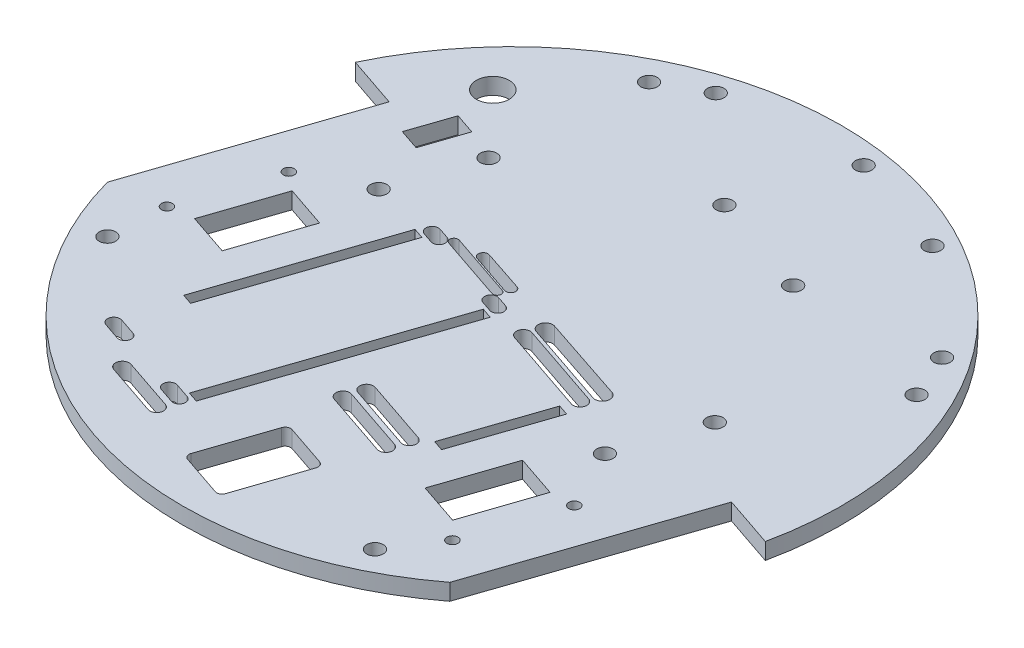
SolidWorks part; units mm, degrees
ref_plane "Alzado" through (0, 0, 0) normal (0, 0, 1) x (1, 0, 0)
ref_plane "Planta" through (0, 0, 0) normal (0, 1, 0) x (1, 0, 0)
ref_plane "Vista lateral" through (0, 0, 0) normal (1, 0, 0) x (0, 0, -1)
sketch "Croquis1" plane through (0, 0, 0) normal (0, 1, 0) x (1, 0, 0)
  line L12 (-65.7777, 23.2819) -> (-63.8527, 28.9647) construction
  line L13 (-25.7128, -75.9069) -> (39.5136, 116.648) construction
  line L15 (-54.221, 25.6922) -> (-44.913, 22.5392)
  line L16 (-44.913, 22.5392) -> (-57.8902, -15.771)
  line L17 (31.3298, -24.3939) -> (26.8382, -37.6538)
  line L18 (23.7528, -21.8272) -> (31.3298, -24.3939)
  line L19 (19.2611, -35.0871) -> (23.7528, -21.8272)
  line L20 (26.8382, -37.6538) -> (19.2611, -35.0871)
  line L21 (58.6729, -12.5497) -> (49.3649, -9.3967)
  line L22 (49.3649, -9.3967) -> (36.3876, -47.7068)
  line L32 (-2.2423, -26.9718) -> (9.5969, -30.9822)
  line L35 (4.6864, -0.2832) -> (20.3144, -5.577)
  line L36 (12.8273, -26.9004) -> (14.7216, -27.5421)
  line L38 (-3.0293, -29.3446) -> (8.7948, -33.35)
  line L39 (14.3923, -30.0726) -> (21.7715, -8.2885) construction
  line L41 (-44.197, -13.5912) -> (-36.6199, -16.1579)
  line L42 (-36.6199, -16.1579) -> (-32.1282, -2.898)
  line L43 (-32.1282, -2.898) -> (-39.7053, -0.3313)
  line L44 (-39.7053, -0.3313) -> (-44.197, -13.5912)
  line L45 (-44.197, -13.5912) -> (-36.6199, -16.1579)
  line L46 (-36.6199, -16.1579) -> (-32.1282, -2.898)
  line L47 (-32.1282, -2.898) -> (-39.7053, -0.3313)
  line L48 (-39.7053, -0.3313) -> (-44.197, -13.5912)
  line L51 (-27.8165, -44.7147) -> (-18.3452, -47.923)
  line L52 (-17.5431, -45.5552) -> (-27.0144, -42.3468)
  line L53 (14.7216, -27.5421) -> (20.4815, -10.5382)
  line L54 (20.4815, -10.5382) -> (18.5872, -9.8965)
  line L55 (18.5872, -9.8965) -> (12.8273, -26.9004)
  line L56 (-20.551, 4.1412) -> (-22.4453, 4.7829)
  line L57 (-10.7116, 5.3544) -> (-20.551, -23.6924) construction
  line L61 (-2.2537, 2.4893) -> (-19.1695, 8.2194) construction
  line L62 (-35.5833, -38.381) -> (-32.4839, -39.4309)
  line L63 (-22.4453, 4.7829) -> (-33.1017, -26.6759)
  line L64 (-33.1017, -26.6759) -> (-31.2074, -27.3176)
  line L65 (-31.2074, -27.3176) -> (-20.551, 4.1412)
  line L66 (-1.7409, -2.2305) -> (-12.3973, -33.6894)
  line L67 (-3.6352, -1.5889) -> (-1.7409, -2.2305)
  line L68 (-14.2916, -33.0477) -> (-3.6352, -1.5889)
  line L70 (-14.2916, -33.0477) -> (-17.1766, -41.5646)
  line L71 (-17.1766, -41.5646) -> (-15.2823, -42.2063)
  line L72 (-15.2823, -42.2063) -> (-12.3973, -33.6894)
  line L73 (-35.2168, 17.7539) -> (-32.6502, 25.331)
  line L74 (-7.4858, -50.9251) -> (-3.315, -38.6123)
  line L75 (-2.047, -37.986) -> (5.5301, -40.5527)
  line L76 (6.1564, -41.8207) -> (1.9855, -54.1334)
  line L77 (-6.8595, -52.193) -> (0.7176, -54.7597)
  line L78 (-32.6502, 25.331) -> (-36.4387, 26.6144)
  line L79 (-36.4387, 26.6144) -> (-39.0054, 19.0373)
  line L80 (-39.0054, 19.0373) -> (-35.2168, 17.7539)
  line L81 (-34.8498, -36.2158) -> (-31.7504, -37.2657)
  line L82 (-1.1514, -23.7515) -> (10.6878, -27.762)
  line L83 (-1.9535, -26.1194) -> (9.8857, -30.1298)
  line L84 (3.6918, -3.22) -> (19.3196, -8.5138)
  line L85 (4.4939, -0.8522) -> (20.1216, -6.1459)
  line L86 (-20.1813, 7.0872) -> (-18.287, 6.4455)
  line L87 (-20.9147, 4.922) -> (-19.0204, 4.2804)
  line L88 (-4.0326, 1.617) -> (-2.1384, 0.9753)
  line L89 (-4.7661, -0.5482) -> (-2.8718, -1.1899)
  line L90 (-19.5441, -41.4005) -> (-16.8069, -42.3277)
  line L91 (-20.2776, -43.5657) -> (-17.5403, -44.4929)
  line L92 (5.531, 2.2337) -> (21.1922, -2.9834)
  line L93 (-12.2339, 5.87) -> (-4.6568, 3.3034)
  line L95 (-11.6756, 7.5336) -> (-4.0842, 5.0097)
  line L97 (28.503, -1.2073) -> (-24.5366, 16.7594) construction
  line L98 (-16.734, 7.1163) -> (-4.8605, 3.1084)
  line L99 (-17.2138, 5.6951) -> (-5.3402, 1.6872)
  arc A0 (-57.8902, -15.771) -> (36.3876, -47.7068) centre (0, 0) ccw
  circle A1 centre (-48.6272, -14.2022) radius 1
  circle A2 centre (-43.0126, 2.3727) radius 1
  circle A5 centre (35.5996, -24.2566) radius 1
  circle A6 centre (29.985, -40.8314) radius 1
  arc A9 (58.6729, -12.5497) -> (-54.221, 25.6922) centre (0, 0) ccw
  arc A10 (-27.0144, -42.3468) -> (-27.8165, -44.7147) centre (-27.4155, -43.5307) ccw
  arc A12 (-18.3452, -47.923) -> (-17.5431, -45.5552) centre (-17.9441, -46.7391) ccw
  arc A14 (-32.4839, -39.4309) -> (-31.7504, -37.2657) centre (-32.1172, -38.3483) ccw
  arc A16 (-19.5441, -41.4005) -> (-20.2776, -43.5657) centre (-19.9108, -42.4831) ccw
  circle A18 centre (-24.3574, 49.3124) radius 1.5 construction
  circle A19 centre (49.3124, 24.3574) radius 1.5 construction
  circle A20 centre (24.3574, -49.3124) radius 1.5 construction
  circle A21 centre (-49.3124, -24.3574) radius 1.5 construction
  circle A22 centre (-24.3574, 49.3124) radius 1.5
  circle A23 centre (49.3124, 24.3574) radius 1.5
  circle A24 centre (24.3574, -49.3124) radius 1.5
  circle A25 centre (-49.3124, -24.3574) radius 1.5
  circle A27 centre (-32.0854, 7.8009) radius 1.5
  circle A28 centre (30.221, -13.3049) radius 1.5
  circle A30 centre (-17.1736, -43.4103) radius 1.143 construction
  circle A31 centre (45.7525, 32.5521) radius 1.5 construction
  circle A32 centre (45.7525, 32.5521) radius 1.5
  circle A33 centre (-35.2166, -37.2984) radius 1.143 construction
  circle A35 centre (-16.552, 53.6572) radius 1.5
  circle A36 centre (35.283, 1.6449) radius 1.5 construction
  circle A37 centre (-27.0196, 22.7494) radius 1.5 construction
  circle A38 centre (35.283, 1.6449) radius 1.5
  circle A39 centre (-27.0196, 22.7494) radius 1.5
  circle A40 centre (-1.5525, -24.9354) radius 1.25 construction
  circle A41 centre (10.2867, -28.9459) radius 1.25 construction
  circle A42 centre (19.7206, -7.3299) radius 1.25 construction
  circle A43 centre (4.0929, -2.0361) radius 1.25 construction
  circle A44 centre (-2.5051, -0.1073) radius 1.143 construction
  circle A45 centre (-20.548, 6.0046) radius 1.143 construction
  arc A46 (-17.5403, -44.4929) -> (-16.8069, -42.3277) centre (-17.1736, -43.4103) ccw
  arc A47 (-34.8498, -36.2158) -> (-35.5833, -38.381) centre (-35.2166, -37.2984) ccw
  arc A48 (-1.1514, -23.7515) -> (-1.9535, -26.1194) centre (-1.5525, -24.9354) ccw
  arc A49 (9.8857, -30.1298) -> (10.6878, -27.762) centre (10.2867, -28.9459) ccw
  arc A50 (19.3196, -8.5138) -> (20.1216, -6.1459) centre (19.7206, -7.3299) ccw
  arc A51 (4.4939, -0.8522) -> (3.6918, -3.22) centre (4.0929, -2.0361) ccw
  arc A52 (-2.8718, -1.1899) -> (-2.1384, 0.9753) centre (-2.5051, -0.1073) ccw
  arc A53 (-20.1813, 7.0872) -> (-20.9147, 4.922) centre (-20.548, 6.0046) ccw
  arc A56 (20.3144, -5.577) -> (21.1922, -2.9834) centre (20.7533, -4.2802) ccw
  arc A57 (-2.2423, -26.9718) -> (-3.0293, -29.3446) centre (-2.6433, -28.1557) ccw
  arc A58 (8.7948, -33.35) -> (9.5969, -30.9822) centre (9.1959, -32.1661) ccw
  arc A61 (1.9855, -54.1334) -> (0.7176, -54.7597) centre (1.0384, -53.8126) cw
  arc A62 (-7.4858, -50.9251) -> (-6.8595, -52.193) centre (-6.5387, -51.2459) ccw
  arc A63 (-3.315, -38.6123) -> (-2.047, -37.986) centre (-2.3678, -38.9332) cw
  arc A64 (5.5301, -40.5527) -> (6.1564, -41.8207) centre (5.2092, -41.4998) cw
  circle A71 centre (8.3151, 55.7156) radius 1.5
  circle A72 centre (27.2578, 49.299) radius 1.5
  circle A74 centre (20.8411, 30.3563) radius 1.5
  circle A75 centre (1.8984, 36.7729) radius 1.5
  arc A76 (-4.0326, 1.617) -> (-4.7661, -0.5482) centre (-4.3993, 0.5344) ccw
  arc A78 (5.531, 2.2337) -> (4.6864, -0.2832) centre (5.1123, 0.9741) ccw
  arc A81 (-19.0204, 4.2804) -> (-18.287, 6.4455) centre (-18.6537, 5.3629) ccw
  arc A83 (-16.734, 7.1163) -> (-17.2138, 5.6951) centre (-16.9739, 6.4057) ccw
  arc A85 (-11.6756, 7.5336) -> (-12.2339, 5.87) centre (-11.9524, 6.701) ccw
  arc A86 (-4.6568, 3.3034) -> (-4.0842, 5.0097) centre (-4.3681, 4.1558) ccw
  arc A87 (-5.3402, 1.6872) -> (-4.8605, 3.1084) centre (-5.1003, 2.3978) ccw
  circle A88 centre (-37.3662, 33.8676) radius 3
  point P44 (29.985, -40.8314)
  point P151 (-7.8067, -51.8722)
  point P154 (-2.9941, -37.6652)
  point P157 (6.4772, -40.8735)
  dimension "D1" = 120
  dimension "D8" = 3
  dimension "D10" = 9.8275
  dimension "D11" = 3
  dimension "D13" = 2
  dimension "D15" = 3.4
  dimension "D16" = 2.5
  dimension "D17" = 2.5
  dimension "D20" = 1.5
  dimension "D21" = 20.7533
  dimension "D26" = 10
  dimension "D29" = 1
  dimension "D32" = 7.38
  dimension "D33" = 3
  dimension "D34" = 3
  dimension "D35" = 3
  dimension "D36" = 3
  dimension "D19" = 1.5
  dimension "D25" = 5.6
  dimension "D39" = 6
  dimension "D7" = 20
  dimension "D5" = 6
  dimension "D12" = 16.5
  dimension "D14" = 3.4
  dimension "D18" = 2
  dimension "D22" = 0.5
  dimension "D23" = 2
  dimension "D24" = 15
  dimension "D27" = 2
  dimension "D28" = 10
  dimension "D30" = 8
  dimension "D31" = 4
  dimension "D4" = 2
  dimension "D6" = 10
  dimension "D37" = 8
  dimension "D38" = 1
  dimension "D9" = 2.5
extrude "Saliente-Extruir1" add sketch "Croquis1" along normal blind 3
